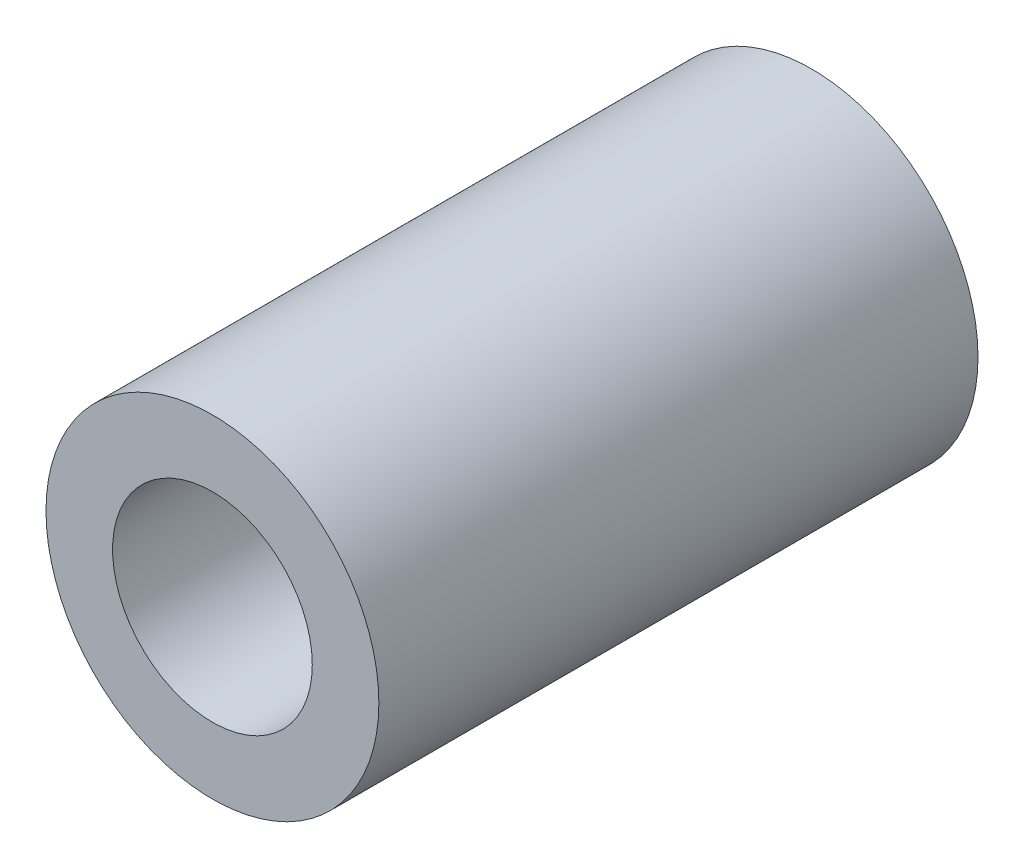
SolidWorks part; units mm, degrees
ref_plane "前视基准面" through (0, 0, 0) normal (0, 0, 1) x (1, 0, 0)
ref_plane "上视基准面" through (0, 0, 0) normal (0, 1, 0) x (1, 0, 0)
ref_plane "右视基准面" through (0, 0, 0) normal (1, 0, 0) x (0, 0, -1)
sketch "草图1" plane through (0, 0, 0) normal (0, 0, 1) x (1, 0, 0)
  circle A0 centre (0, 0) radius 5
  circle A1 centre (0, 0) radius 3
  dimension "D1" = 10
  dimension "D2" = 6
extrude "凸台-拉伸1" add sketch "草图1" along normal blind 18
